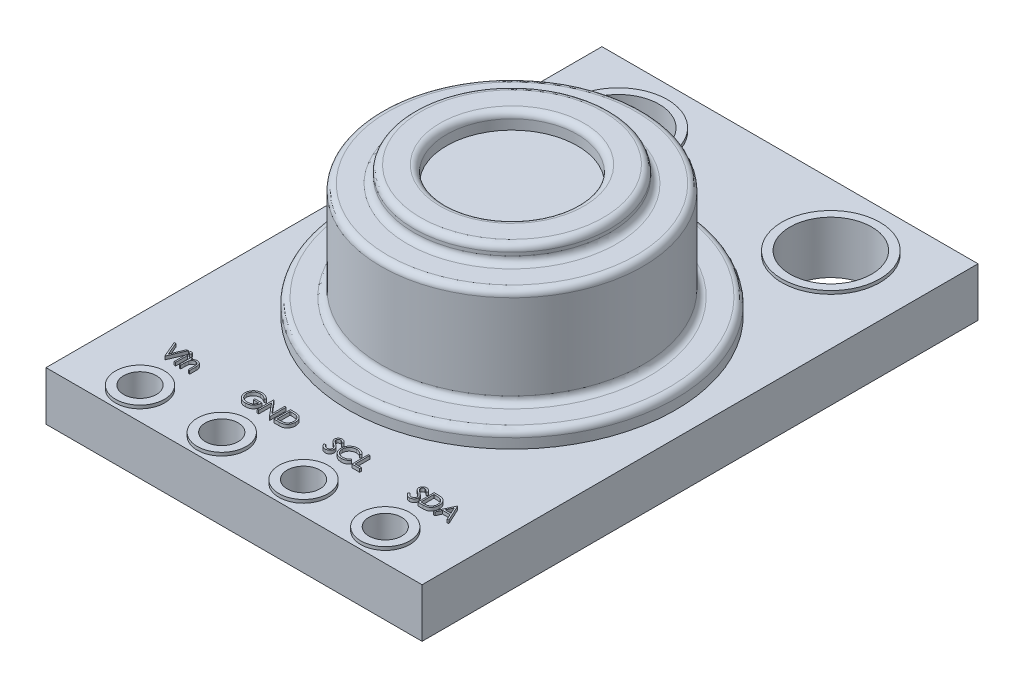
SolidWorks part; units mm, degrees
ref_plane "Plano frontal" through (0, 0, 0) normal (0, 0, 1) x (1, 0, 0)
ref_plane "Plano superior" through (0, 0, 0) normal (0, 1, 0) x (1, 0, 0)
ref_plane "Plano direito" through (0, 0, 0) normal (1, 0, 0) x (0, 0, -1)
sketch "Esboço1" plane through (0, 0, 0) normal (0, 1, 0) x (1, 0, 0)
  line L5 (0, 0) -> (11.5, 0)
  line L6 (0, 0) -> (0, 17)
  line L7 (0, 17) -> (11.5, 17)
  line L8 (11.5, 0) -> (11.5, 17)
  dimension "D1" = 17
  dimension "D2" = 11.5
extrude "Ressalto-extrusão1" add sketch "Esboço1" along normal blind 1.5
sketch "Esboço4" plane through (0, 1.5, 0) normal (0, 1, 0) x (1, 0, 0)
  line L0 (0, 17) -> (11.5, 0) construction
  circle A0 centre (5.75, 8.5) radius 5
extrude "Ressalto-extrusão2" add sketch "Esboço4" along normal blind 0.5
sketch "Esboço5" plane through (0, 2, 0) normal (0, 1, 0) x (1, 0, 0)
  circle A0 centre (5.75, 8.5) radius 4
  circle A1 centre (5.75, 8.5) radius 5
  circle A2 centre (5.75, 8.5) radius 5
  dimension "D1" = 0
  dimension "D2" = 1
extrude "Ressalto-extrusão3" add sketch "Esboço5" along normal blind 3 contours A0
sketch "Esboço6" plane through (0, 5, 0) normal (0, 1, 0) x (1, 0, 0)
  circle A0 centre (5.75, 8.5) radius 3
  circle A1 centre (5.75, 8.5) radius 4
  circle A2 centre (5.75, 8.5) radius 4
  dimension "D1" = 0
  dimension "D2" = 1
extrude "Ressalto-extrusão4" add sketch "Esboço6" along normal blind 0.5 contours A0
sketch "Esboço7" plane through (0, 5.5, 0) normal (0, 1, 0) x (1, 0, 0)
  circle A0 centre (5.75, 8.5) radius 2
  circle A1 centre (5.75, 8.5) radius 3
  circle A2 centre (5.75, 8.5) radius 3
  dimension "D1" = 0
  dimension "D2" = 1
extrude "Corte-extrusão1" cut sketch "Esboço7" against normal blind 0.5 contours A0
fillet "Filete1" radius 0.2 6 edges at (5.75, 2, -3.5) (5.75, 2, -4.5) (5.75, 5, -4.5) (5.75, 5, -5.5) (5.75, 5.5, -5.5) (5.75, 5.5, -6.5)
sketch "Esboço8" plane through (0, 1.5, 0) normal (0, 1, 0) x (1, 0, 0)
  line L0 (0, 17) -> (2.5, 17) construction
  line L1 (11.5, 17) -> (0, 17) construction
  line L2 (11.5, 17) -> (9, 17) construction
  line L3 (9, 17) -> (9, 15) construction
  line L4 (2.5, 17) -> (2.5, 15) construction
  line L5 (5.75, 0) -> (5.75, 3.5) construction
  line L6 (0, 0) -> (11.5, 0) construction
  line L7 (5.75, 0) -> (5.75, 1.75) construction
  line L9 (4.5, 0.875) -> (2, 0.875) construction
  line L10 (7, 0.875) -> (9.5, 0.875) construction
  circle A0 centre (2.5, 15) radius 1.5
  circle A1 centre (9, 15) radius 1.5
  circle A2 centre (2.5, 15) radius 1.25
  circle A3 centre (9, 15) radius 1.25
  circle A4 centre (5.75, 8.5) radius 5 construction
  circle A5 centre (4.5, 0.875) radius 0.5
  circle A6 centre (2, 0.875) radius 0.5
  circle A7 centre (4.5, 0.875) radius 0.75
  circle A8 centre (2, 0.875) radius 0.75
  circle A9 centre (9.5, 0.875) radius 0.75
  circle A10 centre (7, 0.875) radius 0.75
  circle A11 centre (9.5, 0.875) radius 0.5
  circle A12 centre (7, 0.875) radius 0.5
  point P25 (5.75, 0.875)
  dimension "D1" = 2.5
  dimension "D2" = 3
  dimension "D3" = 6.5
  dimension "D5" = 2.5
  dimension "D6" = 1
  dimension "D4" = 2
  dimension "D7" = 0.25
extrude "Ressalto-extrusão5" add sketch "Esboço8" along normal blind 0.1
sketch "Esboço9" plane through (0, 1.5, 0) normal (0, 1, 0) x (1, 0, 0)
  circle A0 centre (9.5, 0.875) radius 0.5 construction
  circle A1 centre (7, 0.875) radius 0.5 construction
  circle A2 centre (4.5, 0.875) radius 0.5 construction
  circle A3 centre (2, 0.875) radius 0.5 construction
  circle A4 centre (9, 15) radius 1.25 construction
  circle A5 centre (2.5, 15) radius 1.25 construction
  circle A6 centre (9.5, 0.875) radius 0.5
  circle A7 centre (7, 0.875) radius 0.5
  circle A8 centre (4.5, 0.875) radius 0.5
  circle A9 centre (2, 0.875) radius 0.5
  circle A10 centre (9, 15) radius 1.25
  circle A11 centre (2.5, 15) radius 1.25
extrude "Corte-extrusão4" cut sketch "Esboço9" against normal blind 3
sketch "Esboço10" plane through (0, 1.5, 0) normal (0, 1, 0) x (1, 0, 0)
  line L0 (0, 2.0236) -> (11.5, 2.0236) construction
  line L1 (0, 17) -> (0, 0) construction
  line L2 (11.5, 0) -> (11.5, 17) construction
  text T0 " Vin       GND     SCL       SDA" font "Century Gothic" height 0.5
extrude "Ressalto-extrusão6" add sketch "Esboço10" along normal blind 0.1
